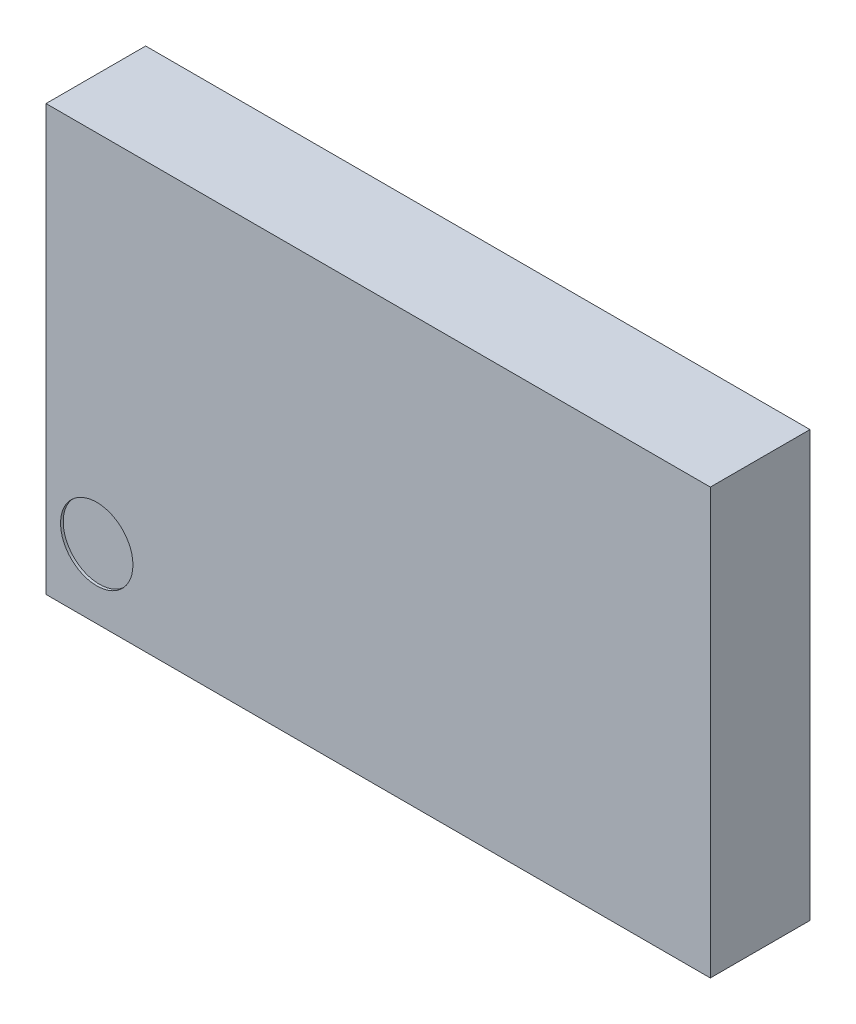
SolidWorks part; units mm, degrees
ref_plane "Front Plane" through (0, 0, 0) normal (0, 0, 1) x (1, 0, 0)
ref_plane "Top Plane" through (0, 0, 0) normal (0, 1, 0) x (1, 0, 0)
ref_plane "Right Plane" through (0, 0, 0) normal (1, 0, 0) x (0, 0, -1)
sketch "Sketch1" plane through (0, 0, 0) normal (0, 0, 1) x (1, 0, 0)
  line L1 (-2.5, -1.6) -> (2.5, -1.6)
  line L2 (-2.5, -1.6) -> (-2.5, 1.6)
  line L3 (-2.5, 1.6) -> (2.5, 1.6)
  line L4 (2.5, -1.6) -> (2.5, 1.6)
  line L5 (-2.5, -1.6) -> (2.5, 1.6) construction
  line L6 (-2.5, 1.6) -> (2.5, -1.6) construction
  point P0 (0, 0)
  dimension "D1" = 3.2
  dimension "D2" = 5
extrude "Boss-Extrude1" add sketch "Sketch1" along normal blind 0.75
sketch "Sketch2" plane through (0, 0, 0) normal (0, 0, -1) x (-1, 0, 0)
  line L0 (-1.27, 0.5662) -> (-1.27, 1.4662) construction
  line L1 (-1.54, 1.4662) -> (-1, 1.4662)
  line L2 (-1.59, 1.4162) -> (-1.59, 0.7162)
  line L3 (-1.44, 0.5662) -> (-1.1, 0.5662)
  line L4 (-0.95, 1.4162) -> (-0.95, 0.7162)
  arc A0 (-1.59, 0.7162) -> (-1.44, 0.5662) centre (-1.44, 0.7162) ccw
  arc A1 (-1.1, 0.5662) -> (-0.95, 0.7162) centre (-1.1, 0.7162) ccw
  arc A2 (-1.54, 1.4662) -> (-1.59, 1.4162) centre (-1.54, 1.4162) ccw
  arc A3 (-1, 1.4662) -> (-0.95, 1.4162) centre (-1, 1.4162) cw
  point P11 (-0.95, 0.5662)
  point P14 (-1.59, 1.4662)
  point P17 (-0.95, 1.4662)
  dimension "D4" = 0.15
  dimension "D5" = 0.05
  dimension "D1" = 0.9
  dimension "D2" = 0.64
  dimension "D3" = 1.27
extrude "Boss-Extrude2" add sketch "Sketch2" along normal blind 0.02 contours L4 A1 L3 A0 L2 A2 L1 A3
pattern_linear "LPattern1" count 3 spacing 1.27 along (-1, 0, 0) of "Boss-Extrude2"
mirror "Mirror1" about plane through (0, 0, 0) normal (0, 1, 0) of "LPattern1", "Boss-Extrude2"
sketch "Sketch3" plane through (0, 0, 0.75) normal (0, 0, 1) x (1, 0, 0)
  circle A0 centre (-2.1183, -1.0805) radius 0.2724
extrude "Cut-Extrude1" cut sketch "Sketch3" against normal blind 0.02
